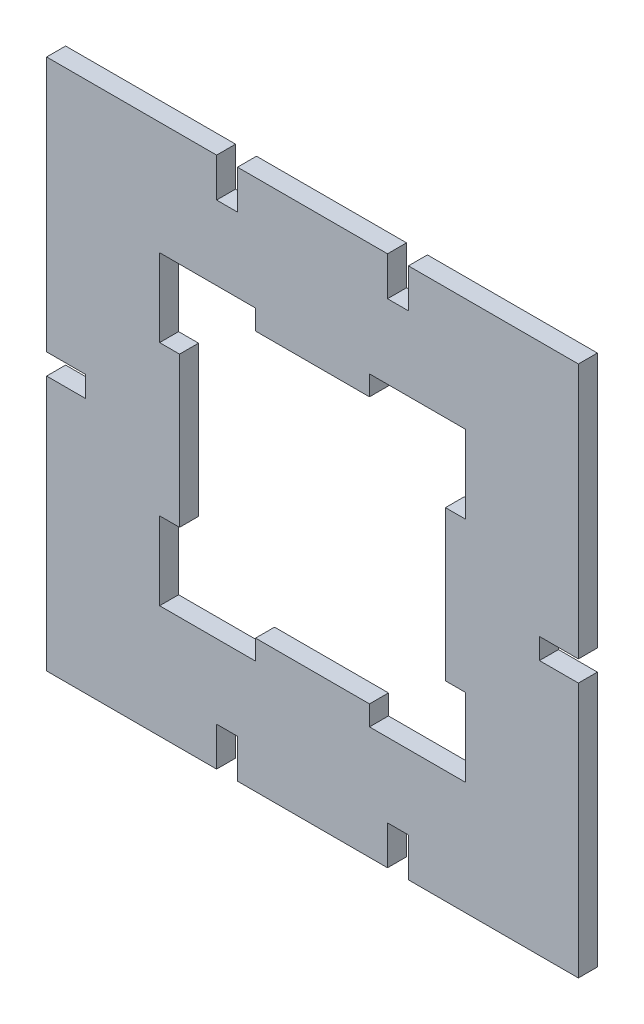
SolidWorks part; units mm, degrees
material "Plain Carbon Steel"
ref_plane "Front Plane" through (0, 0, 0) normal (0, 0, 1) x (1, 0, 0)
ref_plane "Top Plane" through (0, 0, 0) normal (0, 1, 0) x (1, 0, 0)
ref_plane "Right Plane" through (0, 0, 0) normal (1, 0, 0) x (0, 0, -1)
sketch "Model" plane through (0, 0, 0) normal (0, 0, 1) x (1, 0, 0)
  line L0 (-936.253, -13.7291) -> (-891.503, -13.7291)
  line L1 (-796.253, -80.9791) -> (-796.253, -13.7291)
  line L2 (-901.253, -103.4791) -> (-901.253, -63.9791)
  line L3 (-826.003, -63.9791) -> (-831.253, -63.9791)
  line L4 (-881.253, -48.7291) -> (-851.253, -48.7291)
  line L5 (-936.253, -80.9791) -> (-926.003, -80.9791)
  line L6 (-936.253, -153.7291) -> (-891.503, -153.7291)
  line L7 (-826.003, -43.4791) -> (-826.003, -63.9791)
  line L8 (-881.253, -43.4791) -> (-906.503, -43.4791)
  line L9 (-936.253, -80.9791) -> (-936.253, -13.7291)
  line L10 (-886.003, -153.7291) -> (-886.003, -143.4791)
  line L11 (-846.503, -153.7291) -> (-846.503, -143.4791)
  line L12 (-846.503, -143.4791) -> (-841.003, -143.4791)
  line L13 (-846.503, -23.9791) -> (-841.003, -23.9791)
  line L14 (-891.503, -143.4791) -> (-891.503, -153.7291)
  line L15 (-826.003, -103.4791) -> (-831.253, -103.4791)
  line L16 (-806.503, -80.9791) -> (-806.503, -86.4791)
  line L17 (-841.003, -143.4791) -> (-841.003, -153.7291)
  line L18 (-826.003, -123.9791) -> (-826.003, -103.4791)
  line L19 (-796.253, -153.7291) -> (-841.003, -153.7291)
  line L20 (-846.503, -13.7291) -> (-846.503, -23.9791)
  line L21 (-886.003, -143.4791) -> (-891.503, -143.4791)
  line L22 (-926.003, -80.9791) -> (-926.003, -86.4791)
  line L23 (-796.253, -13.7291) -> (-841.003, -13.7291)
  line L24 (-891.503, -23.9791) -> (-891.503, -13.7291)
  line L25 (-926.003, -86.4791) -> (-936.253, -86.4791)
  line L26 (-796.253, -80.9791) -> (-806.503, -80.9791)
  line L27 (-886.003, -13.7291) -> (-886.003, -23.9791)
  line L28 (-851.253, -123.9791) -> (-826.003, -123.9791)
  line L29 (-906.503, -43.4791) -> (-906.503, -63.9791)
  line L30 (-881.253, -118.7291) -> (-851.253, -118.7291)
  line L31 (-906.503, -123.9791) -> (-906.503, -103.4791)
  line L32 (-906.503, -63.9791) -> (-901.253, -63.9791)
  line L33 (-906.503, -103.4791) -> (-901.253, -103.4791)
  line L34 (-806.503, -86.4791) -> (-796.253, -86.4791)
  line L35 (-841.003, -23.9791) -> (-841.003, -13.7291)
  line L36 (-886.003, -13.7291) -> (-846.503, -13.7291)
  line L37 (-886.003, -23.9791) -> (-891.503, -23.9791)
  line L38 (-936.253, -153.7291) -> (-936.253, -86.4791)
  line L39 (-886.003, -153.7291) -> (-846.503, -153.7291)
  line L40 (-796.253, -153.7291) -> (-796.253, -86.4791)
  line L41 (-831.253, -103.4791) -> (-831.253, -63.9791)
  line L42 (-851.253, -118.7291) -> (-851.253, -123.9791)
  line L43 (-881.253, -123.9791) -> (-881.253, -118.7291)
  line L44 (-881.253, -123.9791) -> (-906.503, -123.9791)
  line L45 (-881.253, -43.4791) -> (-881.253, -48.7291)
  line L46 (-851.253, -48.7291) -> (-851.253, -43.4791)
  line L47 (-851.253, -43.4791) -> (-826.003, -43.4791)
  line L48 (-922.8243, -143.4791) -> (-906.503, -143.4791)
  line L49 (-918.3287, -141.5176) -> (-918.3287, -140.9057)
  line L50 (-918.3693, -141.7103) -> (-918.3287, -141.5176)
  line L51 (-908.6009, -142.4791) -> (-909.4829, -142.4088)
  line L52 (-922.7845, -134.6328) -> (-922.8243, -134.8247)
  line L53 (-910.8085, -141.71) -> (-910.688, -141.8875)
  line L54 (-914.7197, -133.851) -> (-915.9435, -138.8337)
  line L55 (-918.4911, -141.8891) -> (-918.3693, -141.7103)
  line L56 (-918.9781, -142.2044) -> (-918.4911, -141.8891)
  line L57 (-921.4538, -133.935) -> (-922.1874, -134.1504)
  line L58 (-910.8487, -133.8632) -> (-910.8487, -138.0963)
  line L59 (-910.8487, -138.0963) -> (-910.4117, -137.5874)
  line L60 (-910.8085, -141.71) -> (-910.8487, -141.5176)
  line L61 (-915.9435, -138.8337) -> (-913.4209, -138.8451)
  line L62 (-921.4663, -142.4104) -> (-920.5765, -142.4791)
  line L63 (-910.8487, -133.8632) -> (-906.503, -133.8632)
  line L64 (-910.4117, -137.5874) -> (-909.9496, -137.3345)
  line L65 (-909.9496, -137.3345) -> (-908.6009, -137.1347)
  line L66 (-918.3287, -134.8247) -> (-918.3693, -134.6374)
  line L67 (-922.8243, -134.8247) -> (-922.8243, -141.5176)
  line L68 (-922.6651, -141.8953) -> (-922.1874, -142.2044)
  line L69 (-920.5765, -142.4791) -> (-919.6899, -142.4104)
  line L70 (-912.4719, -142.4791) -> (-913.4209, -138.8451)
  line L71 (-913.4209, -138.8451) -> (-914.7197, -133.851)
  line L72 (-909.4829, -142.4088) -> (-910.2056, -142.1981)
  line L73 (-922.1874, -142.2044) -> (-921.4663, -142.4104)
  line L74 (-922.6651, -134.4564) -> (-922.7845, -134.6328)
  line L75 (-918.9781, -134.1504) -> (-919.7086, -133.935)
  line L76 (-919.7086, -133.935) -> (-920.5765, -133.8632)
  line L77 (-922.1874, -134.1504) -> (-922.6651, -134.4564)
  line L78 (-922.7845, -141.715) -> (-922.6651, -141.8953)
  line L79 (-910.688, -141.8875) -> (-910.2056, -142.1981)
  line L80 (-918.3287, -134.8247) -> (-918.3287, -135.4366)
  line L81 (-920.5765, -133.8632) -> (-921.4538, -133.935)
  line L82 (-922.8243, -141.5176) -> (-922.7845, -141.715)
  line L83 (-918.3693, -134.6374) -> (-918.4911, -134.4626)
  line L84 (-919.6899, -142.4104) -> (-918.9781, -142.2044)
  line L85 (-918.4911, -134.4626) -> (-918.9781, -134.1504)
  line L86 (-906.3933, -141.71) -> (-906.5139, -141.8875)
  line L87 (-906.5139, -141.8875) -> (-906.9962, -142.1981)
  line L88 (-906.9962, -137.4156) -> (-906.5139, -137.7263)
  line L89 (-906.9962, -142.1981) -> (-907.7189, -142.4088)
  line L90 (-907.7189, -137.2049) -> (-906.9962, -137.4156)
  line L91 (-908.6009, -137.1347) -> (-907.7189, -137.2049)
  line L92 (-915.9435, -138.8337) -> (-916.8426, -142.4791)
  line L93 (-906.5139, -137.7263) -> (-906.3933, -137.9039)
  line L94 (-906.3531, -141.5176) -> (-906.3933, -141.71)
  line L95 (-907.7189, -142.4088) -> (-908.6009, -142.4791)
  line L96 (-906.3933, -137.9039) -> (-906.3531, -138.0963)
  line L97 (-906.3531, -138.0963) -> (-906.3531, -141.5176)
  line L98 (-866.2429, -16.7002) -> (-865.809, -16.736)
  line L99 (-867.2872, -16.9967) -> (-867.0484, -16.8437)
  line L100 (-865.4437, -16.8437) -> (-865.2002, -16.9998)
  line L101 (-866.6816, -16.736) -> (-867.0484, -16.8437)
  line L102 (-867.3469, -17.0849) -> (-867.3668, -17.1809)
  line L103 (-867.3668, -17.1809) -> (-867.3668, -20.5273)
  line L104 (-867.3668, -20.5273) -> (-867.3469, -20.6261)
  line L105 (-868.1302, -17.0873) -> (-868.1099, -17.1809)
  line L106 (-868.1302, -17.0873) -> (-868.1911, -16.9998)
  line L107 (-867.2872, -16.9967) -> (-867.3469, -17.0849)
  line L108 (-868.4346, -16.8437) -> (-868.7998, -16.736)
  line L109 (-865.2002, -16.9998) -> (-865.1393, -17.0873)
  line L110 (-865.1393, -17.0873) -> (-865.119, -17.1809)
  line L111 (-865.119, -17.1809) -> (-865.119, -17.4868)
  line L112 (-865.4437, -16.8437) -> (-865.809, -16.736)
  line L113 (-868.1099, -17.1809) -> (-868.1099, -17.4868)
  line L114 (-868.1911, -16.9998) -> (-868.4346, -16.8437)
  line L115 (-866.6816, -16.736) -> (-866.2429, -16.7002)
  line L116 (-867.3469, -20.6261) -> (-867.2872, -20.7162)
  line L117 (-867.2872, -20.7162) -> (-867.0484, -20.8707)
  line L118 (-867.0484, -20.8707) -> (-866.6878, -20.9737)
  line L119 (-866.6878, -20.9737) -> (-866.2429, -21.0081)
  line L120 (-866.2429, -21.0081) -> (-865.7996, -20.9737)
  line L121 (-865.7996, -20.9737) -> (-865.4437, -20.8707)
  line L122 (-865.4437, -20.8707) -> (-865.2002, -20.7131)
  line L123 (-870.3378, -20.6261) -> (-870.3577, -20.5273)
  line L124 (-870.3577, -20.5273) -> (-870.3577, -17.1809)
  line L125 (-870.3577, -17.1809) -> (-870.3378, -17.0849)
  line L126 (-870.2781, -16.9967) -> (-870.0392, -16.8437)
  line L127 (-870.0392, -16.8437) -> (-869.6724, -16.736)
  line L128 (-869.6724, -16.736) -> (-869.2338, -16.7002)
  line L129 (-868.1302, -20.6237) -> (-868.1911, -20.7131)
  line L130 (-868.7905, -20.9737) -> (-869.2338, -21.0081)
  line L131 (-870.3378, -17.0849) -> (-870.2781, -16.9967)
  line L132 (-869.2338, -16.7002) -> (-868.7998, -16.736)
  line L133 (-868.1099, -20.2214) -> (-868.1099, -20.5273)
  line L134 (-868.1099, -20.5273) -> (-868.1302, -20.6237)
  line L135 (-869.2338, -21.0081) -> (-869.6787, -20.9737)
  line L136 (-869.6787, -20.9737) -> (-870.0392, -20.8707)
  line L137 (-870.0392, -20.8707) -> (-870.2781, -20.7162)
  line L138 (-868.1911, -20.7131) -> (-868.4346, -20.8707)
  line L139 (-868.4346, -20.8707) -> (-868.7905, -20.9737)
  line L140 (-870.2781, -20.7162) -> (-870.3378, -20.6261)
  line L141 (-862.4497, -20.8676) -> (-862.8111, -20.973)
  line L142 (-865.2002, -20.7131) -> (-865.1393, -20.6237)
  line L143 (-865.119, -20.5273) -> (-865.119, -20.2214)
  line L144 (-862.8111, -18.371) -> (-863.2521, -18.3359)
  line L145 (-864.3559, -20.6235) -> (-864.376, -20.5273)
  line L146 (-863.9264, -18.4358) -> (-864.1575, -18.5622)
  line L147 (-863.6931, -20.973) -> (-864.0544, -20.8676)
  line L148 (-862.2086, -20.7123) -> (-862.4497, -20.8676)
  line L149 (-863.2521, -18.3359) -> (-863.9264, -18.4358)
  line L150 (-864.376, -16.7002) -> (-864.376, -18.8167)
  line L151 (-862.8111, -20.973) -> (-863.2521, -21.0081)
  line L152 (-862.2031, -16.7002) -> (-864.376, -16.7002)
  line L153 (-864.0544, -20.8676) -> (-864.2956, -20.7123)
  line L154 (-862.1483, -20.6235) -> (-862.2086, -20.7123)
  line L155 (-862.1483, -20.6235) -> (-862.1282, -20.5273)
  line L156 (-862.2086, -18.6317) -> (-862.1483, -18.7205)
  line L157 (-862.2086, -18.6317) -> (-862.4497, -18.4764)
  line L158 (-864.376, -18.8167) -> (-864.1575, -18.5622)
  line L159 (-862.8111, -18.371) -> (-862.4497, -18.4764)
  line L160 (-862.1282, -18.8167) -> (-862.1282, -20.5273)
  line L161 (-862.1483, -18.7205) -> (-862.1282, -18.8167)
  line L162 (-863.2521, -21.0081) -> (-863.6931, -20.973)
  line L163 (-865.1393, -20.6237) -> (-865.119, -20.5273)
  line L164 (-864.3559, -20.6235) -> (-864.2956, -20.7123)
  line L165 (-872.8577, -18.8541) -> (-877.8577, -18.8541)
  line L166 (-875.8577, -17.8541) -> (-877.8577, -18.8541)
  line L167 (-875.8577, -19.8541) -> (-877.8577, -18.8541)
  line L168 (-859.6483, -18.8541) -> (-854.6483, -18.8541)
  line L169 (-856.6483, -19.8541) -> (-854.6483, -18.8541)
  line L170 (-856.6483, -17.8541) -> (-854.6483, -18.8541)
  line L171 (-908.253, -83.7291) -> (-903.253, -83.7291)
  line L172 (-905.253, -84.7291) -> (-903.253, -83.7291)
  line L173 (-905.253, -82.7291) -> (-903.253, -83.7291)
  line L174 (-916.7408, -85.0964) -> (-916.7408, -85.4023)
  line L175 (-916.7408, -85.4023) -> (-916.7611, -85.4987)
  line L176 (-916.7611, -85.4987) -> (-916.822, -85.5881)
  line L177 (-916.822, -85.5881) -> (-917.0655, -85.7457)
  line L178 (-917.0655, -85.7457) -> (-917.4214, -85.8487)
  line L179 (-917.4214, -85.8487) -> (-917.8647, -85.8831)
  line L180 (-917.8647, -85.8831) -> (-918.3096, -85.8487)
  line L181 (-918.3096, -85.8487) -> (-918.6701, -85.7457)
  line L182 (-918.6701, -85.7457) -> (-918.909, -85.5912)
  line L183 (-918.909, -85.5912) -> (-918.9687, -85.501)
  line L184 (-918.9687, -85.501) -> (-918.9886, -85.4023)
  line L185 (-918.9886, -85.4023) -> (-918.9886, -82.0559)
  line L186 (-918.9886, -82.0559) -> (-918.9687, -81.9599)
  line L187 (-918.9687, -81.9599) -> (-918.909, -81.8717)
  line L188 (-918.909, -81.8717) -> (-918.6701, -81.7187)
  line L189 (-918.6701, -81.7187) -> (-918.3033, -81.611)
  line L190 (-918.3033, -81.611) -> (-917.8647, -81.5751)
  line L191 (-917.8647, -81.5751) -> (-917.4307, -81.611)
  line L192 (-917.4307, -81.611) -> (-917.0655, -81.7187)
  line L193 (-917.0655, -81.7187) -> (-916.822, -81.8748)
  line L194 (-916.822, -81.8748) -> (-916.7611, -81.9622)
  line L195 (-916.7611, -81.9622) -> (-916.7408, -82.0559)
  line L196 (-916.7408, -82.0559) -> (-916.7408, -82.3618)
  line L197 (-916.7408, -82.3618) -> (-916.7408, -82.0559)
  line L198 (-916.7408, -82.0559) -> (-916.7611, -81.9622)
  line L199 (-916.7611, -81.9622) -> (-916.822, -81.8748)
  line L200 (-916.822, -81.8748) -> (-917.0655, -81.7187)
  line L201 (-917.0655, -81.7187) -> (-917.4307, -81.611)
  line L202 (-917.4307, -81.611) -> (-917.8647, -81.5751)
  line L203 (-917.8647, -81.5751) -> (-918.3033, -81.611)
  line L204 (-918.3033, -81.611) -> (-918.6701, -81.7187)
  line L205 (-918.6701, -81.7187) -> (-918.909, -81.8717)
  line L206 (-918.909, -81.8717) -> (-918.9687, -81.9599)
  line L207 (-918.9687, -81.9599) -> (-918.9886, -82.0559)
  line L208 (-918.9886, -82.0559) -> (-918.9886, -85.4023)
  line L209 (-918.9886, -85.4023) -> (-918.9687, -85.501)
  line L210 (-918.9687, -85.501) -> (-918.909, -85.5912)
  line L211 (-918.909, -85.5912) -> (-918.6701, -85.7457)
  line L212 (-918.6701, -85.7457) -> (-918.3096, -85.8487)
  line L213 (-918.3096, -85.8487) -> (-917.8647, -85.8831)
  line L214 (-917.8647, -85.8831) -> (-917.4214, -85.8487)
  line L215 (-917.4214, -85.8487) -> (-917.0655, -85.7457)
  line L216 (-917.0655, -85.7457) -> (-916.822, -85.5881)
  line L217 (-916.822, -85.5881) -> (-916.7611, -85.4987)
  line L218 (-916.7611, -85.4987) -> (-916.7408, -85.4023)
  line L219 (-916.7408, -85.4023) -> (-916.7408, -85.0964)
  line L220 (-915.9977, -85.8831) -> (-915.9977, -81.5751)
  line L221 (-915.9977, -81.5751) -> (-913.8685, -81.5751)
  line L222 (-913.8685, -81.5751) -> (-915.9977, -81.5751)
  line L223 (-915.9977, -81.5751) -> (-915.9977, -83.6666)
  line L224 (-915.9977, -83.6666) -> (-914.1683, -83.6666)
  line L225 (-914.1683, -83.6666) -> (-915.9977, -83.6666)
  line L226 (-915.9977, -83.6666) -> (-915.9977, -85.8831)
  line L227 (-915.9977, -85.8831) -> (-913.8685, -85.8831)
  line L228 (-913.8685, -85.8831) -> (-915.9977, -85.8831)
  line L229 (-911.8769, -85.8831) -> (-912.3179, -85.8479)
  line L230 (-912.3179, -85.8479) -> (-912.6792, -85.7426)
  line L231 (-912.6792, -85.7426) -> (-912.9204, -85.5873)
  line L232 (-912.9204, -85.5873) -> (-912.9807, -85.4985)
  line L233 (-912.9807, -85.4985) -> (-913.0008, -85.4023)
  line L234 (-913.0008, -85.4023) -> (-912.9807, -85.4985)
  line L235 (-912.9807, -85.4985) -> (-912.9204, -85.5873)
  line L236 (-912.9204, -85.5873) -> (-912.6792, -85.7426)
  line L237 (-911.0745, -85.7426) -> (-910.8334, -85.5873)
  line L238 (-910.8334, -85.5873) -> (-910.7731, -85.4985)
  line L239 (-910.7731, -85.4985) -> (-910.753, -85.4023)
  line L240 (-910.753, -85.4023) -> (-910.753, -83.6917)
  line L241 (-910.753, -83.6917) -> (-910.7731, -83.5954)
  line L242 (-910.7731, -83.5954) -> (-910.8334, -83.5067)
  line L243 (-910.8334, -83.5067) -> (-911.0745, -83.3513)
  line L244 (-911.0745, -83.3513) -> (-911.4359, -83.246)
  line L245 (-911.4359, -83.246) -> (-911.8769, -83.2109)
  line L246 (-911.8769, -83.2109) -> (-912.5512, -83.3108)
  line L247 (-912.5512, -83.3108) -> (-912.7823, -83.4372)
  line L248 (-912.7823, -83.4372) -> (-913.0008, -83.6917)
  line L249 (-913.0008, -83.6917) -> (-913.0008, -81.5751)
  line L250 (-913.0008, -81.5751) -> (-910.8279, -81.5751)
  line L251 (-910.8279, -81.5751) -> (-913.0008, -81.5751)
  line L252 (-913.0008, -81.5751) -> (-913.0008, -83.6917)
  line L253 (-913.0008, -83.6917) -> (-912.7823, -83.4372)
  line L254 (-912.7823, -83.4372) -> (-912.5512, -83.3108)
  line L255 (-912.5512, -83.3108) -> (-911.8769, -83.2109)
  line L256 (-911.8769, -83.2109) -> (-911.4359, -83.246)
  line L257 (-911.4359, -83.246) -> (-911.0745, -83.3513)
  line L258 (-911.0745, -83.3513) -> (-910.8334, -83.5067)
  line L259 (-910.8334, -83.5067) -> (-910.7731, -83.5954)
  line L260 (-910.7731, -83.5954) -> (-910.753, -83.6917)
  line L261 (-910.753, -83.6917) -> (-910.753, -85.4023)
  line L262 (-910.753, -85.4023) -> (-910.7731, -85.4985)
  line L263 (-910.7731, -85.4985) -> (-910.8334, -85.5873)
  line L264 (-910.8334, -85.5873) -> (-911.0745, -85.7426)
  line L265 (-911.0745, -85.7426) -> (-911.4359, -85.8479)
  line L266 (-911.4359, -85.8479) -> (-911.8769, -85.8831)
  line L267 (-866.253, -126.9791) -> (-866.253, -121.9791)
  line L268 (-865.253, -123.9791) -> (-866.253, -121.9791)
  line L269 (-867.253, -123.9791) -> (-866.253, -121.9791)
  line L270 (-868.123, -131.5003) -> (-868.123, -131.8063)
  line L271 (-868.123, -131.8063) -> (-868.1433, -131.9026)
  line L272 (-868.1433, -131.9026) -> (-868.2041, -131.992)
  line L273 (-868.2041, -131.992) -> (-868.4477, -132.1497)
  line L274 (-868.4477, -132.1497) -> (-868.8036, -132.2527)
  line L275 (-868.8036, -132.2527) -> (-869.2469, -132.287)
  line L276 (-869.2469, -132.287) -> (-869.6918, -132.2527)
  line L277 (-869.6918, -132.2527) -> (-870.0523, -132.1497)
  line L278 (-870.0523, -132.1497) -> (-870.2912, -131.9951)
  line L279 (-870.2912, -131.9951) -> (-870.3509, -131.905)
  line L280 (-870.3509, -131.905) -> (-870.3708, -131.8063)
  line L281 (-870.3708, -131.8063) -> (-870.3708, -128.4598)
  line L282 (-870.3708, -128.4598) -> (-870.3509, -128.3638)
  line L283 (-870.3509, -128.3638) -> (-870.2912, -128.2757)
  line L284 (-870.2912, -128.2757) -> (-870.0523, -128.1227)
  line L285 (-870.0523, -128.1227) -> (-869.6855, -128.015)
  line L286 (-869.6855, -128.015) -> (-869.2469, -127.9791)
  line L287 (-869.2469, -127.9791) -> (-868.8129, -128.015)
  line L288 (-868.8129, -128.015) -> (-868.4477, -128.1227)
  line L289 (-868.4477, -128.1227) -> (-868.2041, -128.2788)
  line L290 (-868.2041, -128.2788) -> (-868.1433, -128.3662)
  line L291 (-868.1433, -128.3662) -> (-868.123, -128.4598)
  line L292 (-868.123, -128.4598) -> (-868.123, -128.7658)
  line L293 (-868.123, -128.7658) -> (-868.123, -128.4598)
  line L294 (-868.123, -128.4598) -> (-868.1433, -128.3662)
  line L295 (-868.1433, -128.3662) -> (-868.2041, -128.2788)
  line L296 (-868.2041, -128.2788) -> (-868.4477, -128.1227)
  line L297 (-868.4477, -128.1227) -> (-868.8129, -128.015)
  line L298 (-868.8129, -128.015) -> (-869.2469, -127.9791)
  line L299 (-869.2469, -127.9791) -> (-869.6855, -128.015)
  line L300 (-869.6855, -128.015) -> (-870.0523, -128.1227)
  line L301 (-870.0523, -128.1227) -> (-870.2912, -128.2757)
  line L302 (-870.2912, -128.2757) -> (-870.3509, -128.3638)
  line L303 (-870.3509, -128.3638) -> (-870.3708, -128.4598)
  line L304 (-870.3708, -128.4598) -> (-870.3708, -131.8063)
  line L305 (-870.3708, -131.8063) -> (-870.3509, -131.905)
  line L306 (-870.3509, -131.905) -> (-870.2912, -131.9951)
  line L307 (-870.2912, -131.9951) -> (-870.0523, -132.1497)
  line L308 (-870.0523, -132.1497) -> (-869.6918, -132.2527)
  line L309 (-869.6918, -132.2527) -> (-869.2469, -132.287)
  line L310 (-869.2469, -132.287) -> (-868.8036, -132.2527)
  line L311 (-868.8036, -132.2527) -> (-868.4477, -132.1497)
  line L312 (-868.4477, -132.1497) -> (-868.2041, -131.992)
  line L313 (-868.2041, -131.992) -> (-868.1433, -131.9026)
  line L314 (-868.1433, -131.9026) -> (-868.123, -131.8063)
  line L315 (-868.123, -131.8063) -> (-868.123, -131.5003)
  line L316 (-867.3799, -132.287) -> (-867.3799, -127.9791)
  line L317 (-867.3799, -127.9791) -> (-866.3622, -127.9791)
  line L318 (-866.3622, -127.9791) -> (-865.9282, -128.015)
  line L319 (-865.9282, -128.015) -> (-865.563, -128.1227)
  line L320 (-865.563, -128.1227) -> (-865.3194, -128.2788)
  line L321 (-865.3194, -128.2788) -> (-865.2585, -128.3662)
  line L322 (-865.2585, -128.3662) -> (-865.2383, -128.4598)
  line L323 (-865.2383, -128.4598) -> (-865.2383, -131.8063)
  line L324 (-865.2383, -131.8063) -> (-865.2585, -131.9026)
  line L325 (-865.2585, -131.9026) -> (-865.3194, -131.992)
  line L326 (-865.3194, -131.992) -> (-865.563, -132.1497)
  line L327 (-865.563, -132.1497) -> (-865.9189, -132.2527)
  line L328 (-865.9189, -132.2527) -> (-866.3622, -132.287)
  line L329 (-866.3622, -132.287) -> (-867.3799, -132.287)
  line L330 (-867.3799, -127.9791) -> (-867.3799, -132.287)
  line L331 (-867.3799, -132.287) -> (-866.3622, -132.287)
  line L332 (-866.3622, -132.287) -> (-865.9189, -132.2527)
  line L333 (-865.9189, -132.2527) -> (-865.563, -132.1497)
  line L334 (-865.563, -132.1497) -> (-865.3194, -131.992)
  line L335 (-865.3194, -131.992) -> (-865.2585, -131.9026)
  line L336 (-865.2585, -131.9026) -> (-865.2383, -131.8063)
  line L337 (-865.2383, -131.8063) -> (-865.2383, -128.4598)
  line L338 (-865.2383, -128.4598) -> (-865.2585, -128.3662)
  line L339 (-865.2585, -128.3662) -> (-865.3194, -128.2788)
  line L340 (-865.3194, -128.2788) -> (-865.563, -128.1227)
  line L341 (-865.563, -128.1227) -> (-865.9282, -128.015)
  line L342 (-865.9282, -128.015) -> (-866.3622, -127.9791)
  line L343 (-866.3622, -127.9791) -> (-867.3799, -127.9791)
  line L344 (-863.2591, -132.287) -> (-863.7001, -132.2519)
  line L345 (-863.7001, -132.2519) -> (-864.0614, -132.1465)
  line L346 (-864.0614, -132.1465) -> (-864.3026, -131.9912)
  line L347 (-864.3026, -131.9912) -> (-864.3629, -131.9024)
  line L348 (-864.3629, -131.9024) -> (-864.383, -131.8063)
  line L349 (-864.383, -131.8063) -> (-864.3629, -131.9024)
  line L350 (-864.3629, -131.9024) -> (-864.3026, -131.9912)
  line L351 (-864.3026, -131.9912) -> (-864.0614, -132.1465)
  line L352 (-862.4567, -132.1465) -> (-862.2156, -131.9912)
  line L353 (-862.2156, -131.9912) -> (-862.1553, -131.9024)
  line L354 (-862.1553, -131.9024) -> (-862.1352, -131.8063)
  line L355 (-862.1352, -131.8063) -> (-862.1352, -130.0956)
  line L356 (-862.1352, -130.0956) -> (-862.1553, -129.9994)
  line L357 (-862.1553, -129.9994) -> (-862.2156, -129.9106)
  line L358 (-862.2156, -129.9106) -> (-862.4567, -129.7553)
  line L359 (-862.4567, -129.7553) -> (-862.8181, -129.6499)
  line L360 (-862.8181, -129.6499) -> (-863.2591, -129.6148)
  line L361 (-863.2591, -129.6148) -> (-863.9334, -129.7147)
  line L362 (-863.9334, -129.7147) -> (-864.1645, -129.8412)
  line L363 (-864.1645, -129.8412) -> (-864.383, -130.0956)
  line L364 (-864.383, -130.0956) -> (-864.383, -127.9791)
  line L365 (-864.383, -127.9791) -> (-862.2101, -127.9791)
  line L366 (-862.2101, -127.9791) -> (-864.383, -127.9791)
  line L367 (-864.383, -127.9791) -> (-864.383, -130.0956)
  line L368 (-864.383, -130.0956) -> (-864.1645, -129.8412)
  line L369 (-864.1645, -129.8412) -> (-863.9334, -129.7147)
  line L370 (-863.9334, -129.7147) -> (-863.2591, -129.6148)
  line L371 (-863.2591, -129.6148) -> (-862.8181, -129.6499)
  line L372 (-862.8181, -129.6499) -> (-862.4567, -129.7553)
  line L373 (-862.4567, -129.7553) -> (-862.2156, -129.9106)
  line L374 (-862.2156, -129.9106) -> (-862.1553, -129.9994)
  line L375 (-862.1553, -129.9994) -> (-862.1352, -130.0956)
  line L376 (-862.1352, -130.0956) -> (-862.1352, -131.8063)
  line L377 (-862.1352, -131.8063) -> (-862.1553, -131.9024)
  line L378 (-862.1553, -131.9024) -> (-862.2156, -131.9912)
  line L379 (-862.2156, -131.9912) -> (-862.4567, -132.1465)
  line L380 (-862.4567, -132.1465) -> (-862.8181, -132.2519)
  line L381 (-862.8181, -132.2519) -> (-863.2591, -132.287)
  line L382 (-801.378, -73.9791) -> (-801.378, -78.9791)
  line L383 (-802.378, -76.9791) -> (-801.378, -78.9791)
  line L384 (-800.378, -76.9791) -> (-801.378, -78.9791)
  line L385 (-812.7951, -78.8418) -> (-812.4346, -78.9448)
  line L386 (-811.1905, -78.8418) -> (-810.947, -78.6841)
  line L387 (-810.947, -78.6841) -> (-810.8861, -78.5947)
  line L388 (-812.7951, -78.8418) -> (-813.034, -78.6872)
  line L389 (-813.0937, -78.5971) -> (-813.1136, -78.4983)
  line L390 (-810.8658, -75.4579) -> (-810.8658, -75.1519)
  line L391 (-811.1905, -74.8148) -> (-811.5557, -74.7071)
  line L392 (-812.4346, -78.9448) -> (-811.9897, -78.9791)
  line L393 (-813.0937, -75.0559) -> (-813.034, -74.9677)
  line L394 (-811.1905, -78.8418) -> (-811.5464, -78.9448)
  line L395 (-813.034, -74.9677) -> (-812.7951, -74.8148)
  line L396 (-811.9897, -74.6712) -> (-812.4283, -74.7071)
  line L397 (-813.034, -78.6872) -> (-813.0937, -78.5971)
  line L398 (-810.8658, -78.4983) -> (-810.8861, -78.5947)
  line L399 (-813.1136, -78.4983) -> (-813.1136, -75.1519)
  line L400 (-813.1136, -75.1519) -> (-813.0937, -75.0559)
  line L401 (-810.8658, -78.1924) -> (-810.8658, -78.4983)
  line L402 (-810.947, -74.9709) -> (-810.8861, -75.0583)
  line L403 (-811.5464, -78.9448) -> (-811.9897, -78.9791)
  line L404 (-810.8658, -75.1519) -> (-810.8861, -75.0583)
  line L405 (-810.947, -74.9709) -> (-811.1905, -74.8148)
  line L406 (-811.5557, -74.7071) -> (-811.9897, -74.6712)
  line L407 (-812.4283, -74.7071) -> (-812.7951, -74.8148)
  line L408 (-809.105, -74.6712) -> (-808.6757, -74.7071)
  line L409 (-808.0017, -78.597) -> (-807.9811, -78.4983)
  line L410 (-807.9811, -75.152) -> (-808.0017, -75.0583)
  line L411 (-810.1227, -74.6712) -> (-810.1227, -76.7813)
  line L412 (-807.9811, -77.2433) -> (-808.0388, -77.0903)
  line L413 (-806.0019, -78.9791) -> (-806.4429, -78.944)
  line L414 (-807.1258, -78.4983) -> (-807.1057, -78.5945)
  line L415 (-808.5477, -76.8499) -> (-809.105, -76.7813)
  line L416 (-808.6757, -74.7071) -> (-808.312, -74.8148)
  line L417 (-804.9529, -74.6712) -> (-807.1258, -74.6712)
  line L418 (-808.312, -78.8417) -> (-808.6726, -78.9448)
  line L419 (-808.2121, -76.9561) -> (-808.5477, -76.8499)
  line L420 (-808.0638, -74.9709) -> (-808.0017, -75.0583)
  line L421 (-808.0388, -76.474) -> (-808.2121, -76.6129)
  line L422 (-806.4429, -78.944) -> (-806.8042, -78.8386)
  line L423 (-810.1227, -74.6712) -> (-809.105, -74.6712)
  line L424 (-809.105, -78.9791) -> (-808.6726, -78.9448)
  line L425 (-807.9811, -78.4983) -> (-807.9811, -77.2433)
  line L426 (-808.0388, -77.0903) -> (-808.2121, -76.9561)
  line L427 (-807.0454, -78.6833) -> (-807.1057, -78.5945)
  line L428 (-807.9811, -76.3196) -> (-807.9811, -75.152)
  line L429 (-809.105, -76.7813) -> (-810.1227, -76.7813)
  line L430 (-810.1227, -78.9791) -> (-809.105, -78.9791)
  line L431 (-808.554, -76.7175) -> (-809.105, -76.7813)
  line L432 (-808.554, -76.7175) -> (-808.2121, -76.6129)
  line L433 (-808.0638, -74.9709) -> (-808.312, -74.8148)
  line L434 (-807.9811, -76.3196) -> (-808.0388, -76.474)
  line L435 (-806.8042, -78.8386) -> (-807.0454, -78.6833)
  line L436 (-808.312, -78.8417) -> (-808.0638, -78.6872)
  line L437 (-808.0017, -78.597) -> (-808.0638, -78.6872)
  line L438 (-804.878, -76.7877) -> (-804.878, -78.4983)
  line L439 (-804.9584, -78.6833) -> (-805.1995, -78.8386)
  line L440 (-806.0019, -76.3069) -> (-805.5609, -76.342)
  line L441 (-807.1258, -76.7877) -> (-806.9073, -76.5332)
  line L442 (-805.1995, -78.8386) -> (-805.5609, -78.944)
  line L443 (-806.6762, -76.4068) -> (-806.0019, -76.3069)
  line L444 (-805.1995, -76.4474) -> (-804.9584, -76.6027)
  line L445 (-805.5609, -78.944) -> (-806.0019, -78.9791)
  line L446 (-804.9584, -76.6027) -> (-804.8981, -76.6915)
  line L447 (-807.1258, -74.6712) -> (-807.1258, -76.7877)
  line L448 (-810.1227, -76.7813) -> (-810.1227, -78.9791)
  line L449 (-804.8981, -76.6915) -> (-804.878, -76.7877)
  line L450 (-804.878, -78.4983) -> (-804.8981, -78.5945)
  line L451 (-805.5609, -76.342) -> (-805.1995, -76.4474)
  line L452 (-804.8981, -78.5945) -> (-804.9584, -78.6833)
  line L453 (-806.9073, -76.5332) -> (-806.6762, -76.4068)
  line L454 (-866.253, -40.4791) -> (-866.253, -45.4791)
  line L455 (-867.253, -43.4791) -> (-866.253, -45.4791)
  line L456 (-865.253, -43.4791) -> (-866.253, -45.4791)
  line L457 (-868.123, -38.6924) -> (-868.123, -38.9984)
  line L458 (-868.123, -38.9984) -> (-868.1433, -39.0947)
  line L459 (-868.1433, -39.0947) -> (-868.2041, -39.1841)
  line L460 (-868.2041, -39.1841) -> (-868.4477, -39.3418)
  line L461 (-868.4477, -39.3418) -> (-868.8036, -39.4448)
  line L462 (-868.8036, -39.4448) -> (-869.2469, -39.4791)
  line L463 (-869.2469, -39.4791) -> (-869.6918, -39.4448)
  line L464 (-869.6918, -39.4448) -> (-870.0523, -39.3418)
  line L465 (-870.0523, -39.3418) -> (-870.2912, -39.1872)
  line L466 (-870.2912, -39.1872) -> (-870.3509, -39.0971)
  line L467 (-870.3509, -39.0971) -> (-870.3708, -38.9984)
  line L468 (-870.3708, -38.9984) -> (-870.3708, -35.6519)
  line L469 (-870.3708, -35.6519) -> (-870.3509, -35.556)
  line L470 (-870.3509, -35.556) -> (-870.2912, -35.4678)
  line L471 (-870.2912, -35.4678) -> (-870.0523, -35.3148)
  line L472 (-870.0523, -35.3148) -> (-869.6855, -35.2071)
  line L473 (-869.6855, -35.2071) -> (-869.2469, -35.1712)
  line L474 (-869.2469, -35.1712) -> (-868.8129, -35.2071)
  line L475 (-868.8129, -35.2071) -> (-868.4477, -35.3148)
  line L476 (-868.4477, -35.3148) -> (-868.2041, -35.4709)
  line L477 (-868.2041, -35.4709) -> (-868.1433, -35.5583)
  line L478 (-868.1433, -35.5583) -> (-868.123, -35.6519)
  line L479 (-868.123, -35.6519) -> (-868.123, -35.9579)
  line L480 (-868.123, -35.9579) -> (-868.123, -35.6519)
  line L481 (-868.123, -35.6519) -> (-868.1433, -35.5583)
  line L482 (-868.1433, -35.5583) -> (-868.2041, -35.4709)
  line L483 (-868.2041, -35.4709) -> (-868.4477, -35.3148)
  line L484 (-868.4477, -35.3148) -> (-868.8129, -35.2071)
  line L485 (-868.8129, -35.2071) -> (-869.2469, -35.1712)
  line L486 (-869.2469, -35.1712) -> (-869.6855, -35.2071)
  line L487 (-869.6855, -35.2071) -> (-870.0523, -35.3148)
  line L488 (-870.0523, -35.3148) -> (-870.2912, -35.4678)
  line L489 (-870.2912, -35.4678) -> (-870.3509, -35.556)
  line L490 (-870.3509, -35.556) -> (-870.3708, -35.6519)
  line L491 (-870.3708, -35.6519) -> (-870.3708, -38.9984)
  line L492 (-870.3708, -38.9984) -> (-870.3509, -39.0971)
  line L493 (-870.3509, -39.0971) -> (-870.2912, -39.1872)
  line L494 (-870.2912, -39.1872) -> (-870.0523, -39.3418)
  line L495 (-870.0523, -39.3418) -> (-869.6918, -39.4448)
  line L496 (-869.6918, -39.4448) -> (-869.2469, -39.4791)
  line L497 (-869.2469, -39.4791) -> (-868.8036, -39.4448)
  line L498 (-868.8036, -39.4448) -> (-868.4477, -39.3418)
  line L499 (-868.4477, -39.3418) -> (-868.2041, -39.1841)
  line L500 (-868.2041, -39.1841) -> (-868.1433, -39.0947)
  line L501 (-868.1433, -39.0947) -> (-868.123, -38.9984)
  line L502 (-868.123, -38.9984) -> (-868.123, -38.6924)
  line L503 (-867.3799, -39.4791) -> (-867.3799, -35.1712)
  line L504 (-867.3799, -35.1712) -> (-866.3622, -35.1712)
  line L505 (-866.3622, -35.1712) -> (-865.9282, -35.2071)
  line L506 (-865.9282, -35.2071) -> (-865.563, -35.3148)
  line L507 (-865.563, -35.3148) -> (-865.3194, -35.4709)
  line L508 (-865.3194, -35.4709) -> (-865.2585, -35.5583)
  line L509 (-865.2585, -35.5583) -> (-865.2383, -35.6519)
  line L510 (-865.2383, -35.6519) -> (-865.2383, -38.9984)
  line L511 (-865.2383, -38.9984) -> (-865.2585, -39.0947)
  line L512 (-865.2585, -39.0947) -> (-865.3194, -39.1841)
  line L513 (-865.3194, -39.1841) -> (-865.563, -39.3418)
  line L514 (-865.563, -39.3418) -> (-865.9189, -39.4448)
  line L515 (-865.9189, -39.4448) -> (-866.3622, -39.4791)
  line L516 (-866.3622, -39.4791) -> (-867.3799, -39.4791)
  line L517 (-867.3799, -35.1712) -> (-867.3799, -39.4791)
  line L518 (-867.3799, -39.4791) -> (-866.3622, -39.4791)
  line L519 (-866.3622, -39.4791) -> (-865.9189, -39.4448)
  line L520 (-865.9189, -39.4448) -> (-865.563, -39.3418)
  line L521 (-865.563, -39.3418) -> (-865.3194, -39.1841)
  line L522 (-865.3194, -39.1841) -> (-865.2585, -39.0947)
  line L523 (-865.2585, -39.0947) -> (-865.2383, -38.9984)
  line L524 (-865.2383, -38.9984) -> (-865.2383, -35.6519)
  line L525 (-865.2383, -35.6519) -> (-865.2585, -35.5583)
  line L526 (-865.2585, -35.5583) -> (-865.3194, -35.4709)
  line L527 (-865.3194, -35.4709) -> (-865.563, -35.3148)
  line L528 (-865.563, -35.3148) -> (-865.9282, -35.2071)
  line L529 (-865.9282, -35.2071) -> (-866.3622, -35.1712)
  line L530 (-866.3622, -35.1712) -> (-867.3799, -35.1712)
  line L531 (-863.2591, -39.4791) -> (-863.7001, -39.444)
  line L532 (-863.7001, -39.444) -> (-864.0614, -39.3386)
  line L533 (-864.0614, -39.3386) -> (-864.3026, -39.1833)
  line L534 (-864.3026, -39.1833) -> (-864.3629, -39.0946)
  line L535 (-864.3629, -39.0946) -> (-864.383, -38.9984)
  line L536 (-864.383, -38.9984) -> (-864.3629, -39.0946)
  line L537 (-864.3629, -39.0946) -> (-864.3026, -39.1833)
  line L538 (-864.3026, -39.1833) -> (-864.0614, -39.3386)
  line L539 (-862.4567, -39.3386) -> (-862.2156, -39.1833)
  line L540 (-862.2156, -39.1833) -> (-862.1553, -39.0946)
  line L541 (-862.1553, -39.0946) -> (-862.1352, -38.9984)
  line L542 (-862.1352, -38.9984) -> (-862.1352, -37.2877)
  line L543 (-862.1352, -37.2877) -> (-862.1553, -37.1915)
  line L544 (-862.1553, -37.1915) -> (-862.2156, -37.1027)
  line L545 (-862.2156, -37.1027) -> (-862.4567, -36.9474)
  line L546 (-862.4567, -36.9474) -> (-862.8181, -36.842)
  line L547 (-862.8181, -36.842) -> (-863.2591, -36.8069)
  line L548 (-863.2591, -36.8069) -> (-863.9334, -36.9068)
  line L549 (-863.9334, -36.9068) -> (-864.1645, -37.0333)
  line L550 (-864.1645, -37.0333) -> (-864.383, -37.2877)
  line L551 (-864.383, -37.2877) -> (-864.383, -35.1712)
  line L552 (-864.383, -35.1712) -> (-862.2101, -35.1712)
  line L553 (-862.2101, -35.1712) -> (-864.383, -35.1712)
  line L554 (-864.383, -35.1712) -> (-864.383, -37.2877)
  line L555 (-864.383, -37.2877) -> (-864.1645, -37.0333)
  line L556 (-864.1645, -37.0333) -> (-863.9334, -36.9068)
  line L557 (-863.9334, -36.9068) -> (-863.2591, -36.8069)
  line L558 (-863.2591, -36.8069) -> (-862.8181, -36.842)
  line L559 (-862.8181, -36.842) -> (-862.4567, -36.9474)
  line L560 (-862.4567, -36.9474) -> (-862.2156, -37.1027)
  line L561 (-862.2156, -37.1027) -> (-862.1553, -37.1915)
  line L562 (-862.1553, -37.1915) -> (-862.1352, -37.2877)
  line L563 (-862.1352, -37.2877) -> (-862.1352, -38.9984)
  line L564 (-862.1352, -38.9984) -> (-862.1553, -39.0946)
  line L565 (-862.1553, -39.0946) -> (-862.2156, -39.1833)
  line L566 (-862.2156, -39.1833) -> (-862.4567, -39.3386)
  line L567 (-862.4567, -39.3386) -> (-862.8181, -39.444)
  line L568 (-862.8181, -39.444) -> (-863.2591, -39.4791)
  line L569 (-866.2429, -146.4501) -> (-865.809, -146.486)
  line L570 (-867.2872, -146.7467) -> (-867.0484, -146.5937)
  line L571 (-865.4437, -146.5937) -> (-865.2002, -146.7498)
  line L572 (-866.6816, -146.486) -> (-867.0484, -146.5937)
  line L573 (-867.3469, -146.8349) -> (-867.3668, -146.9309)
  line L574 (-867.3668, -146.9309) -> (-867.3668, -150.2773)
  line L575 (-867.3668, -150.2773) -> (-867.3469, -150.376)
  line L576 (-868.1302, -146.8372) -> (-868.1099, -146.9309)
  line L577 (-868.1302, -146.8372) -> (-868.1911, -146.7498)
  line L578 (-867.2872, -146.7467) -> (-867.3469, -146.8349)
  line L579 (-868.4346, -146.5937) -> (-868.7998, -146.486)
  line L580 (-865.2002, -146.7498) -> (-865.1393, -146.8372)
  line L581 (-865.1393, -146.8372) -> (-865.119, -146.9309)
  line L582 (-865.119, -146.9309) -> (-865.119, -147.2368)
  line L583 (-865.4437, -146.5937) -> (-865.809, -146.486)
  line L584 (-868.1099, -146.9309) -> (-868.1099, -147.2368)
  line L585 (-868.1911, -146.7498) -> (-868.4346, -146.5937)
  line L586 (-866.6816, -146.486) -> (-866.2429, -146.4501)
  line L587 (-867.3469, -150.376) -> (-867.2872, -150.4662)
  line L588 (-867.2872, -150.4662) -> (-867.0484, -150.6207)
  line L589 (-867.0484, -150.6207) -> (-866.6878, -150.7237)
  line L590 (-866.6878, -150.7237) -> (-866.2429, -150.7581)
  line L591 (-866.2429, -150.7581) -> (-865.7996, -150.7237)
  line L592 (-865.7996, -150.7237) -> (-865.4437, -150.6207)
  line L593 (-865.4437, -150.6207) -> (-865.2002, -150.463)
  line L594 (-870.3378, -150.376) -> (-870.3577, -150.2773)
  line L595 (-870.3577, -150.2773) -> (-870.3577, -146.9309)
  line L596 (-870.3577, -146.9309) -> (-870.3378, -146.8349)
  line L597 (-870.2781, -146.7467) -> (-870.0392, -146.5937)
  line L598 (-870.0392, -146.5937) -> (-869.6724, -146.486)
  line L599 (-869.6724, -146.486) -> (-869.2338, -146.4501)
  line L600 (-868.1302, -150.3737) -> (-868.1911, -150.463)
  line L601 (-868.7905, -150.7237) -> (-869.2338, -150.7581)
  line L602 (-870.3378, -146.8349) -> (-870.2781, -146.7467)
  line L603 (-869.2338, -146.4501) -> (-868.7998, -146.486)
  line L604 (-868.1099, -149.9714) -> (-868.1099, -150.2773)
  line L605 (-868.1099, -150.2773) -> (-868.1302, -150.3737)
  line L606 (-869.2338, -150.7581) -> (-869.6787, -150.7237)
  line L607 (-869.6787, -150.7237) -> (-870.0392, -150.6207)
  line L608 (-870.0392, -150.6207) -> (-870.2781, -150.4662)
  line L609 (-868.1911, -150.463) -> (-868.4346, -150.6207)
  line L610 (-868.4346, -150.6207) -> (-868.7905, -150.7237)
  line L611 (-870.2781, -150.4662) -> (-870.3378, -150.376)
  line L612 (-862.4497, -150.6176) -> (-862.8111, -150.7229)
  line L613 (-865.2002, -150.463) -> (-865.1393, -150.3737)
  line L614 (-865.119, -150.2773) -> (-865.119, -149.9714)
  line L615 (-862.8111, -148.121) -> (-863.2521, -148.0858)
  line L616 (-864.3559, -150.3735) -> (-864.376, -150.2773)
  line L617 (-863.9264, -148.1858) -> (-864.1575, -148.3122)
  line L618 (-863.6931, -150.7229) -> (-864.0544, -150.6176)
  line L619 (-862.2086, -150.4623) -> (-862.4497, -150.6176)
  line L620 (-863.2521, -148.0858) -> (-863.9264, -148.1858)
  line L621 (-864.376, -146.4501) -> (-864.376, -148.5666)
  line L622 (-862.8111, -150.7229) -> (-863.2521, -150.7581)
  line L623 (-862.2031, -146.4501) -> (-864.376, -146.4501)
  line L624 (-864.0544, -150.6176) -> (-864.2956, -150.4623)
  line L625 (-862.1483, -150.3735) -> (-862.2086, -150.4623)
  line L626 (-862.1483, -150.3735) -> (-862.1282, -150.2773)
  line L627 (-862.2086, -148.3816) -> (-862.1483, -148.4704)
  line L628 (-862.2086, -148.3816) -> (-862.4497, -148.2263)
  line L629 (-864.376, -148.5666) -> (-864.1575, -148.3122)
  line L630 (-862.8111, -148.121) -> (-862.4497, -148.2263)
  line L631 (-862.1282, -148.5666) -> (-862.1282, -150.2773)
  line L632 (-862.1483, -148.4704) -> (-862.1282, -148.5666)
  line L633 (-863.2521, -150.7581) -> (-863.6931, -150.7229)
  line L634 (-865.1393, -150.3737) -> (-865.119, -150.2773)
  line L635 (-864.3559, -150.3735) -> (-864.2956, -150.4623)
  line L636 (-872.8577, -148.6041) -> (-877.8577, -148.6041)
  line L637 (-875.8577, -147.6041) -> (-877.8577, -148.6041)
  line L638 (-875.8577, -149.6041) -> (-877.8577, -148.6041)
  line L639 (-859.6483, -148.6041) -> (-854.6483, -148.6041)
  line L640 (-856.6483, -149.6041) -> (-854.6483, -148.6041)
  line L641 (-856.6483, -147.6041) -> (-854.6483, -148.6041)
  line L642 (-931.128, -73.9791) -> (-931.128, -78.9791)
  line L643 (-932.128, -76.9791) -> (-931.128, -78.9791)
  line L644 (-930.128, -76.9791) -> (-931.128, -78.9791)
  line L645 (-927.307, -78.8418) -> (-926.9465, -78.9448)
  line L646 (-925.7024, -78.8418) -> (-925.4589, -78.6841)
  line L647 (-925.4589, -78.6841) -> (-925.398, -78.5947)
  line L648 (-927.307, -78.8418) -> (-927.5459, -78.6872)
  line L649 (-927.6056, -78.5971) -> (-927.6255, -78.4983)
  line L650 (-925.3777, -75.4579) -> (-925.3777, -75.1519)
  line L651 (-925.7024, -74.8148) -> (-926.0677, -74.7071)
  line L652 (-926.9465, -78.9448) -> (-926.5016, -78.9791)
  line L653 (-927.6056, -75.0559) -> (-927.5459, -74.9677)
  line L654 (-925.7024, -78.8418) -> (-926.0583, -78.9448)
  line L655 (-927.5459, -74.9677) -> (-927.307, -74.8148)
  line L656 (-926.5016, -74.6712) -> (-926.9402, -74.7071)
  line L657 (-927.5459, -78.6872) -> (-927.6056, -78.5971)
  line L658 (-925.3777, -78.4983) -> (-925.398, -78.5947)
  line L659 (-927.6255, -78.4983) -> (-927.6255, -75.1519)
  line L660 (-927.6255, -75.1519) -> (-927.6056, -75.0559)
  line L661 (-925.3777, -78.1924) -> (-925.3777, -78.4983)
  line L662 (-925.4589, -74.9709) -> (-925.398, -75.0583)
  line L663 (-926.0583, -78.9448) -> (-926.5016, -78.9791)
  line L664 (-925.3777, -75.1519) -> (-925.398, -75.0583)
  line L665 (-925.4589, -74.9709) -> (-925.7024, -74.8148)
  line L666 (-926.0677, -74.7071) -> (-926.5016, -74.6712)
  line L667 (-926.9402, -74.7071) -> (-927.307, -74.8148)
  line L668 (-923.6169, -74.6712) -> (-923.1876, -74.7071)
  line L669 (-922.5137, -78.597) -> (-922.493, -78.4983)
  line L670 (-922.493, -75.152) -> (-922.5137, -75.0583)
  line L671 (-924.6346, -74.6712) -> (-924.6346, -76.7813)
  line L672 (-922.493, -77.2433) -> (-922.5507, -77.0903)
  line L673 (-920.5138, -78.9791) -> (-920.9548, -78.944)
  line L674 (-921.6377, -78.4983) -> (-921.6176, -78.5945)
  line L675 (-923.0596, -76.8499) -> (-923.6169, -76.7813)
  line L676 (-923.1876, -74.7071) -> (-922.8239, -74.8148)
  line L677 (-919.4648, -74.6712) -> (-921.6377, -74.6712)
  line L678 (-922.8239, -78.8417) -> (-923.1845, -78.9448)
  line L679 (-922.724, -76.9561) -> (-923.0596, -76.8499)
  line L680 (-922.5757, -74.9709) -> (-922.5137, -75.0583)
  line L681 (-922.5507, -76.474) -> (-922.724, -76.6129)
  line L682 (-920.9548, -78.944) -> (-921.3161, -78.8386)
  line L683 (-924.6346, -74.6712) -> (-923.6169, -74.6712)
  line L684 (-923.6169, -78.9791) -> (-923.1845, -78.9448)
  line L685 (-922.493, -78.4983) -> (-922.493, -77.2433)
  line L686 (-922.5507, -77.0903) -> (-922.724, -76.9561)
  line L687 (-921.5573, -78.6833) -> (-921.6176, -78.5945)
  line L688 (-922.493, -76.3196) -> (-922.493, -75.152)
  line L689 (-923.6169, -76.7813) -> (-924.6346, -76.7813)
  line L690 (-924.6346, -78.9791) -> (-923.6169, -78.9791)
  line L691 (-923.0659, -76.7175) -> (-923.6169, -76.7813)
  line L692 (-923.0659, -76.7175) -> (-922.724, -76.6129)
  line L693 (-922.5757, -74.9709) -> (-922.8239, -74.8148)
  line L694 (-922.493, -76.3196) -> (-922.5507, -76.474)
  line L695 (-921.3161, -78.8386) -> (-921.5573, -78.6833)
  line L696 (-922.8239, -78.8417) -> (-922.5757, -78.6872)
  line L697 (-922.5137, -78.597) -> (-922.5757, -78.6872)
  line L698 (-919.3899, -76.7877) -> (-919.3899, -78.4983)
  line L699 (-919.4703, -78.6833) -> (-919.7114, -78.8386)
  line L700 (-920.5138, -76.3069) -> (-920.0728, -76.342)
  line L701 (-921.6377, -76.7877) -> (-921.4192, -76.5332)
  line L702 (-919.7114, -78.8386) -> (-920.0728, -78.944)
  line L703 (-921.1881, -76.4068) -> (-920.5138, -76.3069)
  line L704 (-919.7114, -76.4474) -> (-919.4703, -76.6027)
  line L705 (-920.0728, -78.944) -> (-920.5138, -78.9791)
  line L706 (-919.4703, -76.6027) -> (-919.41, -76.6915)
  line L707 (-921.6377, -74.6712) -> (-921.6377, -76.7877)
  line L708 (-924.6346, -76.7813) -> (-924.6346, -78.9791)
  line L709 (-919.41, -76.6915) -> (-919.3899, -76.7877)
  line L710 (-919.3899, -78.4983) -> (-919.41, -78.5945)
  line L711 (-920.0728, -76.342) -> (-919.7114, -76.4474)
  line L712 (-919.41, -78.5945) -> (-919.4703, -78.6833)
  line L713 (-921.4192, -76.5332) -> (-921.1881, -76.4068)
  line L714 (-824.253, -83.7291) -> (-829.253, -83.7291)
  line L715 (-827.253, -82.7291) -> (-829.253, -83.7291)
  line L716 (-827.253, -84.7291) -> (-829.253, -83.7291)
  line L717 (-819.5052, -85.0964) -> (-819.5052, -85.4023)
  line L718 (-819.5052, -85.4023) -> (-819.5255, -85.4987)
  line L719 (-819.5255, -85.4987) -> (-819.5863, -85.5881)
  line L720 (-819.5863, -85.5881) -> (-819.8299, -85.7457)
  line L721 (-819.8299, -85.7457) -> (-820.1857, -85.8487)
  line L722 (-820.1857, -85.8487) -> (-820.6291, -85.8831)
  line L723 (-820.6291, -85.8831) -> (-821.074, -85.8487)
  line L724 (-821.074, -85.8487) -> (-821.4345, -85.7457)
  line L725 (-821.4345, -85.7457) -> (-821.6734, -85.5912)
  line L726 (-821.6734, -85.5912) -> (-821.7331, -85.501)
  line L727 (-821.7331, -85.501) -> (-821.753, -85.4023)
  line L728 (-821.753, -85.4023) -> (-821.753, -82.0559)
  line L729 (-821.753, -82.0559) -> (-821.7331, -81.9599)
  line L730 (-821.7331, -81.9599) -> (-821.6734, -81.8717)
  line L731 (-821.6734, -81.8717) -> (-821.4345, -81.7187)
  line L732 (-821.4345, -81.7187) -> (-821.0677, -81.611)
  line L733 (-821.0677, -81.611) -> (-820.6291, -81.5751)
  line L734 (-820.6291, -81.5751) -> (-820.1951, -81.611)
  line L735 (-820.1951, -81.611) -> (-819.8299, -81.7187)
  line L736 (-819.8299, -81.7187) -> (-819.5863, -81.8748)
  line L737 (-819.5863, -81.8748) -> (-819.5255, -81.9622)
  line L738 (-819.5255, -81.9622) -> (-819.5052, -82.0559)
  line L739 (-819.5052, -82.0559) -> (-819.5052, -82.3618)
  line L740 (-819.5052, -82.3618) -> (-819.5052, -82.0559)
  line L741 (-819.5052, -82.0559) -> (-819.5255, -81.9622)
  line L742 (-819.5255, -81.9622) -> (-819.5863, -81.8748)
  line L743 (-819.5863, -81.8748) -> (-819.8299, -81.7187)
  line L744 (-819.8299, -81.7187) -> (-820.1951, -81.611)
  line L745 (-820.1951, -81.611) -> (-820.6291, -81.5751)
  line L746 (-820.6291, -81.5751) -> (-821.0677, -81.611)
  line L747 (-821.0677, -81.611) -> (-821.4345, -81.7187)
  line L748 (-821.4345, -81.7187) -> (-821.6734, -81.8717)
  line L749 (-821.6734, -81.8717) -> (-821.7331, -81.9599)
  line L750 (-821.7331, -81.9599) -> (-821.753, -82.0559)
  line L751 (-821.753, -82.0559) -> (-821.753, -85.4023)
  line L752 (-821.753, -85.4023) -> (-821.7331, -85.501)
  line L753 (-821.7331, -85.501) -> (-821.6734, -85.5912)
  line L754 (-821.6734, -85.5912) -> (-821.4345, -85.7457)
  line L755 (-821.4345, -85.7457) -> (-821.074, -85.8487)
  line L756 (-821.074, -85.8487) -> (-820.6291, -85.8831)
  line L757 (-820.6291, -85.8831) -> (-820.1857, -85.8487)
  line L758 (-820.1857, -85.8487) -> (-819.8299, -85.7457)
  line L759 (-819.8299, -85.7457) -> (-819.5863, -85.5881)
  line L760 (-819.5863, -85.5881) -> (-819.5255, -85.4987)
  line L761 (-819.5255, -85.4987) -> (-819.5052, -85.4023)
  line L762 (-819.5052, -85.4023) -> (-819.5052, -85.0964)
  line L763 (-818.7621, -85.8831) -> (-818.7621, -81.5751)
  line L764 (-818.7621, -81.5751) -> (-816.6329, -81.5751)
  line L765 (-816.6329, -81.5751) -> (-818.7621, -81.5751)
  line L766 (-818.7621, -81.5751) -> (-818.7621, -83.6666)
  line L767 (-818.7621, -83.6666) -> (-816.9327, -83.6666)
  line L768 (-816.9327, -83.6666) -> (-818.7621, -83.6666)
  line L769 (-818.7621, -83.6666) -> (-818.7621, -85.8831)
  line L770 (-818.7621, -85.8831) -> (-816.6329, -85.8831)
  line L771 (-816.6329, -85.8831) -> (-818.7621, -85.8831)
  line L772 (-814.6413, -85.8831) -> (-815.0823, -85.8479)
  line L773 (-815.0823, -85.8479) -> (-815.4436, -85.7426)
  line L774 (-815.4436, -85.7426) -> (-815.6848, -85.5873)
  line L775 (-815.6848, -85.5873) -> (-815.7451, -85.4985)
  line L776 (-815.7451, -85.4985) -> (-815.7652, -85.4023)
  line L777 (-815.7652, -85.4023) -> (-815.7451, -85.4985)
  line L778 (-815.7451, -85.4985) -> (-815.6848, -85.5873)
  line L779 (-815.6848, -85.5873) -> (-815.4436, -85.7426)
  line L780 (-813.8389, -85.7426) -> (-813.5977, -85.5873)
  line L781 (-813.5977, -85.5873) -> (-813.5375, -85.4985)
  line L782 (-813.5375, -85.4985) -> (-813.5174, -85.4023)
  line L783 (-813.5174, -85.4023) -> (-813.5174, -83.6917)
  line L784 (-813.5174, -83.6917) -> (-813.5375, -83.5954)
  line L785 (-813.5375, -83.5954) -> (-813.5977, -83.5067)
  line L786 (-813.5977, -83.5067) -> (-813.8389, -83.3513)
  line L787 (-813.8389, -83.3513) -> (-814.2003, -83.246)
  line L788 (-814.2003, -83.246) -> (-814.6413, -83.2109)
  line L789 (-814.6413, -83.2109) -> (-815.3156, -83.3108)
  line L790 (-815.3156, -83.3108) -> (-815.5466, -83.4372)
  line L791 (-815.5466, -83.4372) -> (-815.7652, -83.6917)
  line L792 (-815.7652, -83.6917) -> (-815.7652, -81.5751)
  line L793 (-815.7652, -81.5751) -> (-813.5923, -81.5751)
  line L794 (-813.5923, -81.5751) -> (-815.7652, -81.5751)
  line L795 (-815.7652, -81.5751) -> (-815.7652, -83.6917)
  line L796 (-815.7652, -83.6917) -> (-815.5466, -83.4372)
  line L797 (-815.5466, -83.4372) -> (-815.3156, -83.3108)
  line L798 (-815.3156, -83.3108) -> (-814.6413, -83.2109)
  line L799 (-814.6413, -83.2109) -> (-814.2003, -83.246)
  line L800 (-814.2003, -83.246) -> (-813.8389, -83.3513)
  line L801 (-813.8389, -83.3513) -> (-813.5977, -83.5067)
  line L802 (-813.5977, -83.5067) -> (-813.5375, -83.5954)
  line L803 (-813.5375, -83.5954) -> (-813.5174, -83.6917)
  line L804 (-813.5174, -83.6917) -> (-813.5174, -85.4023)
  line L805 (-813.5174, -85.4023) -> (-813.5375, -85.4985)
  line L806 (-813.5375, -85.4985) -> (-813.5977, -85.5873)
  line L807 (-813.5977, -85.5873) -> (-813.8389, -85.7426)
  line L808 (-813.8389, -85.7426) -> (-814.2003, -85.8479)
  line L809 (-814.2003, -85.8479) -> (-814.6413, -85.8831)
sketch "Sketch2" plane through (0, 0, 0) normal (0, 0, 1) x (1, 0, 0)
  line L0 (-936.253, -80.9791) -> (-936.253, -13.7291) construction
  line L1 (-936.253, -80.9791) -> (-926.003, -80.9791) construction
  line L2 (-926.003, -80.9791) -> (-926.003, -86.4791) construction
  line L3 (-926.003, -86.4791) -> (-936.253, -86.4791) construction
  line L4 (-936.253, -153.7291) -> (-936.253, -86.4791) construction
  line L5 (-936.253, -153.7291) -> (-891.503, -153.7291) construction
  line L6 (-891.503, -143.4791) -> (-891.503, -153.7291) construction
  line L7 (-886.003, -143.4791) -> (-891.503, -143.4791) construction
  line L8 (-886.003, -153.7291) -> (-886.003, -143.4791) construction
  line L9 (-886.003, -153.7291) -> (-846.503, -153.7291) construction
  line L10 (-846.503, -153.7291) -> (-846.503, -143.4791) construction
  line L11 (-846.503, -143.4791) -> (-841.003, -143.4791) construction
  line L12 (-841.003, -143.4791) -> (-841.003, -153.7291) construction
  line L13 (-796.253, -153.7291) -> (-841.003, -153.7291) construction
  line L14 (-796.253, -153.7291) -> (-796.253, -86.4791) construction
  line L15 (-806.503, -86.4791) -> (-796.253, -86.4791) construction
  line L16 (-806.503, -80.9791) -> (-806.503, -86.4791) construction
  line L17 (-796.253, -80.9791) -> (-806.503, -80.9791) construction
  line L18 (-796.253, -80.9791) -> (-796.253, -13.7291) construction
  line L19 (-796.253, -13.7291) -> (-841.003, -13.7291) construction
  line L20 (-841.003, -23.9791) -> (-841.003, -13.7291) construction
  line L21 (-846.503, -23.9791) -> (-841.003, -23.9791) construction
  line L22 (-846.503, -13.7291) -> (-846.503, -23.9791) construction
  line L23 (-886.003, -13.7291) -> (-846.503, -13.7291) construction
  line L24 (-886.003, -13.7291) -> (-886.003, -23.9791) construction
  line L25 (-886.003, -23.9791) -> (-891.503, -23.9791) construction
  line L26 (-891.503, -23.9791) -> (-891.503, -13.7291) construction
  line L27 (-936.253, -13.7291) -> (-891.503, -13.7291) construction
  line L28 (-936.253, -80.9791) -> (-936.253, -13.7291)
  line L29 (-936.253, -80.9791) -> (-926.003, -80.9791)
  line L30 (-926.003, -80.9791) -> (-926.003, -86.4791)
  line L31 (-926.003, -86.4791) -> (-936.253, -86.4791)
  line L32 (-936.253, -153.7291) -> (-936.253, -86.4791)
  line L33 (-936.253, -153.7291) -> (-891.503, -153.7291)
  line L34 (-891.503, -143.4791) -> (-891.503, -153.7291)
  line L35 (-886.003, -143.4791) -> (-891.503, -143.4791)
  line L36 (-886.003, -153.7291) -> (-886.003, -143.4791)
  line L37 (-886.003, -153.7291) -> (-846.503, -153.7291)
  line L38 (-846.503, -153.7291) -> (-846.503, -143.4791)
  line L39 (-846.503, -143.4791) -> (-841.003, -143.4791)
  line L40 (-841.003, -143.4791) -> (-841.003, -153.7291)
  line L41 (-796.253, -153.7291) -> (-841.003, -153.7291)
  line L42 (-796.253, -153.7291) -> (-796.253, -86.4791)
  line L43 (-806.503, -86.4791) -> (-796.253, -86.4791)
  line L44 (-806.503, -80.9791) -> (-806.503, -86.4791)
  line L45 (-796.253, -80.9791) -> (-806.503, -80.9791)
  line L46 (-796.253, -80.9791) -> (-796.253, -13.7291)
  line L47 (-796.253, -13.7291) -> (-841.003, -13.7291)
  line L48 (-841.003, -23.9791) -> (-841.003, -13.7291)
  line L49 (-846.503, -23.9791) -> (-841.003, -23.9791)
  line L50 (-846.503, -13.7291) -> (-846.503, -23.9791)
  line L51 (-886.003, -13.7291) -> (-846.503, -13.7291)
  line L52 (-886.003, -13.7291) -> (-886.003, -23.9791)
  line L53 (-886.003, -23.9791) -> (-891.503, -23.9791)
  line L54 (-891.503, -23.9791) -> (-891.503, -13.7291)
  line L55 (-936.253, -13.7291) -> (-891.503, -13.7291)
  line L56 (-881.253, -43.4791) -> (-881.253, -48.7291) construction
  line L57 (-881.253, -48.7291) -> (-851.253, -48.7291) construction
  line L58 (-851.253, -48.7291) -> (-851.253, -43.4791) construction
  line L59 (-851.253, -43.4791) -> (-826.003, -43.4791) construction
  line L60 (-826.003, -43.4791) -> (-826.003, -63.9791) construction
  line L61 (-826.003, -63.9791) -> (-831.253, -63.9791) construction
  line L62 (-831.253, -103.4791) -> (-831.253, -63.9791) construction
  line L63 (-826.003, -103.4791) -> (-831.253, -103.4791) construction
  line L64 (-826.003, -123.9791) -> (-826.003, -103.4791) construction
  line L65 (-851.253, -123.9791) -> (-826.003, -123.9791) construction
  line L66 (-851.253, -118.7291) -> (-851.253, -123.9791) construction
  line L67 (-881.253, -118.7291) -> (-851.253, -118.7291) construction
  line L68 (-881.253, -123.9791) -> (-881.253, -118.7291) construction
  line L69 (-881.253, -123.9791) -> (-906.503, -123.9791) construction
  line L70 (-906.503, -123.9791) -> (-906.503, -103.4791) construction
  line L71 (-906.503, -103.4791) -> (-901.253, -103.4791) construction
  line L72 (-901.253, -103.4791) -> (-901.253, -63.9791) construction
  line L73 (-906.503, -63.9791) -> (-901.253, -63.9791) construction
  line L74 (-906.503, -43.4791) -> (-906.503, -63.9791) construction
  line L75 (-881.253, -43.4791) -> (-906.503, -43.4791) construction
  line L76 (-881.253, -43.4791) -> (-881.253, -48.7291)
  line L77 (-881.253, -48.7291) -> (-851.253, -48.7291)
  line L78 (-851.253, -48.7291) -> (-851.253, -43.4791)
  line L79 (-851.253, -43.4791) -> (-826.003, -43.4791)
  line L80 (-826.003, -43.4791) -> (-826.003, -63.9791)
  line L81 (-826.003, -63.9791) -> (-831.253, -63.9791)
  line L82 (-831.253, -103.4791) -> (-831.253, -63.9791)
  line L83 (-826.003, -103.4791) -> (-831.253, -103.4791)
  line L84 (-826.003, -123.9791) -> (-826.003, -103.4791)
  line L85 (-851.253, -123.9791) -> (-826.003, -123.9791)
  line L86 (-851.253, -118.7291) -> (-851.253, -123.9791)
  line L87 (-881.253, -118.7291) -> (-851.253, -118.7291)
  line L88 (-881.253, -123.9791) -> (-881.253, -118.7291)
  line L89 (-881.253, -123.9791) -> (-906.503, -123.9791)
  line L90 (-906.503, -123.9791) -> (-906.503, -103.4791)
  line L91 (-906.503, -103.4791) -> (-901.253, -103.4791)
  line L92 (-901.253, -103.4791) -> (-901.253, -63.9791)
  line L93 (-906.503, -63.9791) -> (-901.253, -63.9791)
  line L94 (-906.503, -43.4791) -> (-906.503, -63.9791)
  line L95 (-881.253, -43.4791) -> (-906.503, -43.4791)
  line L96 (-926.003, -83.7291) -> (-866.253, -83.7291) construction
  line L97 (-866.253, -6.8175) -> (-866.253, -83.7291) construction
  point P18 (-866.253, -13.7291)
extrude "Boss-Extrude1" add sketch "Sketch2" along normal mid plane 5
ref_plane "Plane1" through (0, -83.7291, 0) normal (0, 1, 0) x (1, 0, 0)
ref_plane "Plane2" through (-866.253, 0, 0) normal (1, 0, 0) x (0, 0, -1)
